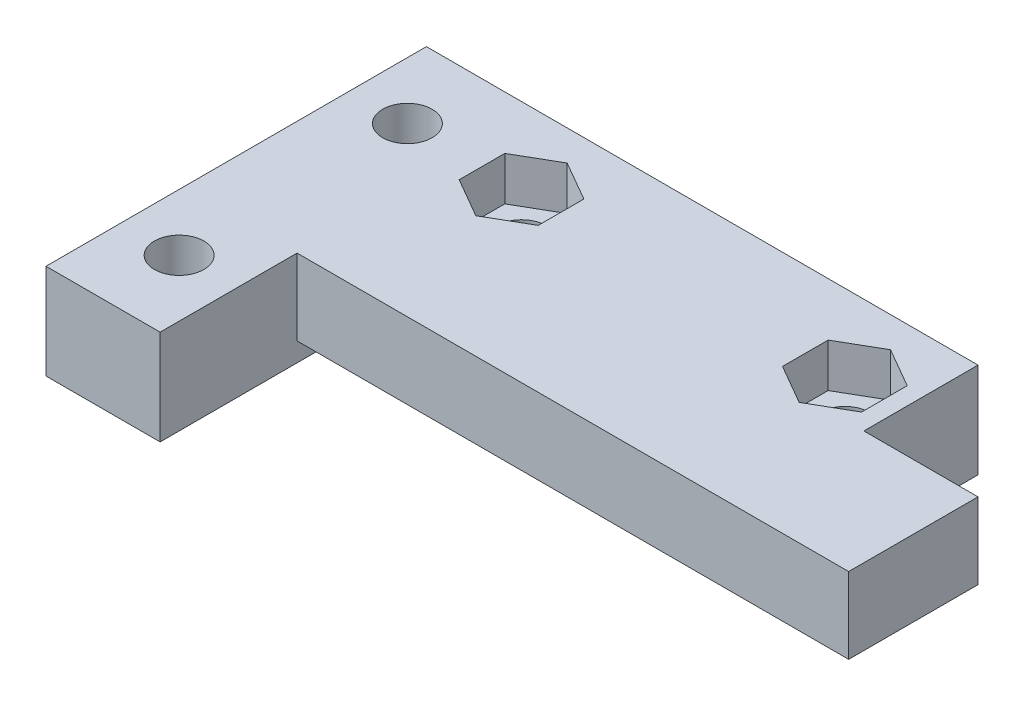
SolidWorks part; units mm, degrees
ref_plane "前基準面" through (0, 0, 0) normal (0, 0, 1) x (1, 0, 0)
ref_plane "上基準面" through (0, 0, 0) normal (0, 1, 0) x (1, 0, 0)
ref_plane "右基準面" through (0, 0, 0) normal (1, 0, 0) x (0, 0, -1)
sketch "草圖1" plane through (0, 0, 0) normal (0, 1, 0) x (1, 0, 0)
  line L1 (0, 0) -> (35, 0)
  line L2 (0, 0) -> (0, 20)
  line L3 (0, 20) -> (35, 20)
  line L4 (35, 0) -> (35, 20)
  dimension "D1" = 35
  dimension "D2" = 20
extrude "填料-伸長1" add sketch "草圖1" along normal blind 5
sketch "草圖2" plane through (0, 0, 0) normal (0, 1, 0) x (1, 0, 0)
  line L0 (0, 20) -> (0, 0) construction
  line L1 (6, 0) -> (35, 0)
  line L2 (6, 0) -> (6, 14)
  line L3 (6, 14) -> (35, 14)
  line L4 (35, 0) -> (35, 14)
  dimension "D1" = 29
  dimension "D2" = 14
  dimension "D3" = 6
  dimension "D4" = 14
extrude "除料-伸長2" cut sketch "草圖2" along normal blind 1
sketch "草圖3" plane through (0, 0, 0) normal (0, 1, 0) x (1, 0, 0)
  line L1 (6, 0) -> (35, 0)
  line L2 (6, 0) -> (6, 7.2)
  line L3 (6, 7.2) -> (35, 7.2)
  line L4 (35, 0) -> (35, 7.2)
  dimension "D1" = 29
  dimension "D2" = 7.2
extrude "除料-伸長4" cut sketch "草圖3" along normal through all
sketch "草圖4" plane through (0, 0, 0) normal (0, 1, 0) x (1, 0, 0)
  line L1 (35, 20) -> (29, 20)
  line L2 (35, 20) -> (35, 14)
  line L3 (35, 14) -> (29, 14)
  line L4 (29, 20) -> (29, 14)
  dimension "D1" = 6
  dimension "D2" = 6
extrude "除料-伸長5" cut sketch "草圖4" along normal through all
sketch "草圖5" plane through (0, 0, 0) normal (0, 1, 0) x (1, 0, 0)
  circle A0 centre (3, 16) radius 1.3
  circle A1 centre (3, 4) radius 1.3
  circle A2 centre (9, 16) radius 1.3
  circle A4 centre (26, 16) radius 1.3
extrude "除料-伸長6" cut sketch "草圖5" along normal through all
sketch "草圖7" plane through (0, 0, 0) normal (0, 1, 0) x (1, 0, 0)
  line L1 (26, 18.4) -> (23.9215, 17.2)
  line L2 (23.9215, 17.2) -> (23.9215, 14.8)
  line L3 (23.9215, 14.8) -> (26, 13.6)
  line L4 (26, 13.6) -> (28.0785, 14.8)
  line L5 (28.0785, 14.8) -> (28.0785, 17.2)
  line L6 (28.0785, 17.2) -> (26, 18.4)
  line L8 (9, 18.4) -> (6.9215, 17.2)
  line L9 (6.9215, 17.2) -> (6.9215, 14.8)
  line L10 (6.9215, 14.8) -> (9, 13.6)
  line L11 (9, 13.6) -> (11.0785, 14.8)
  line L12 (11.0785, 14.8) -> (11.0785, 17.2)
  line L13 (11.0785, 17.2) -> (9, 18.4)
  circle A0 centre (9, 16) radius 2.0785 construction
  circle A1 centre (26, 16) radius 2.0785 construction
  dimension "D1" = 4.8
  dimension "D2" = 4.8
extrude "除料-伸長8" cut sketch "草圖7" against normal blind 2.3 from surface at 5 starting at face at (9, 5, -14.7)
sketch "草圖6" plane through (0, 0, 0) normal (0, 1, 0) x (1, 0, 0)
  circle A1 centre (3, 16) radius 2.2
  circle A2 centre (3, 4) radius 2.2
extrude "除料-伸長10" cut sketch "草圖6" along normal blind 2 from surface at 0 starting at face at (9, 0, -14.7)
